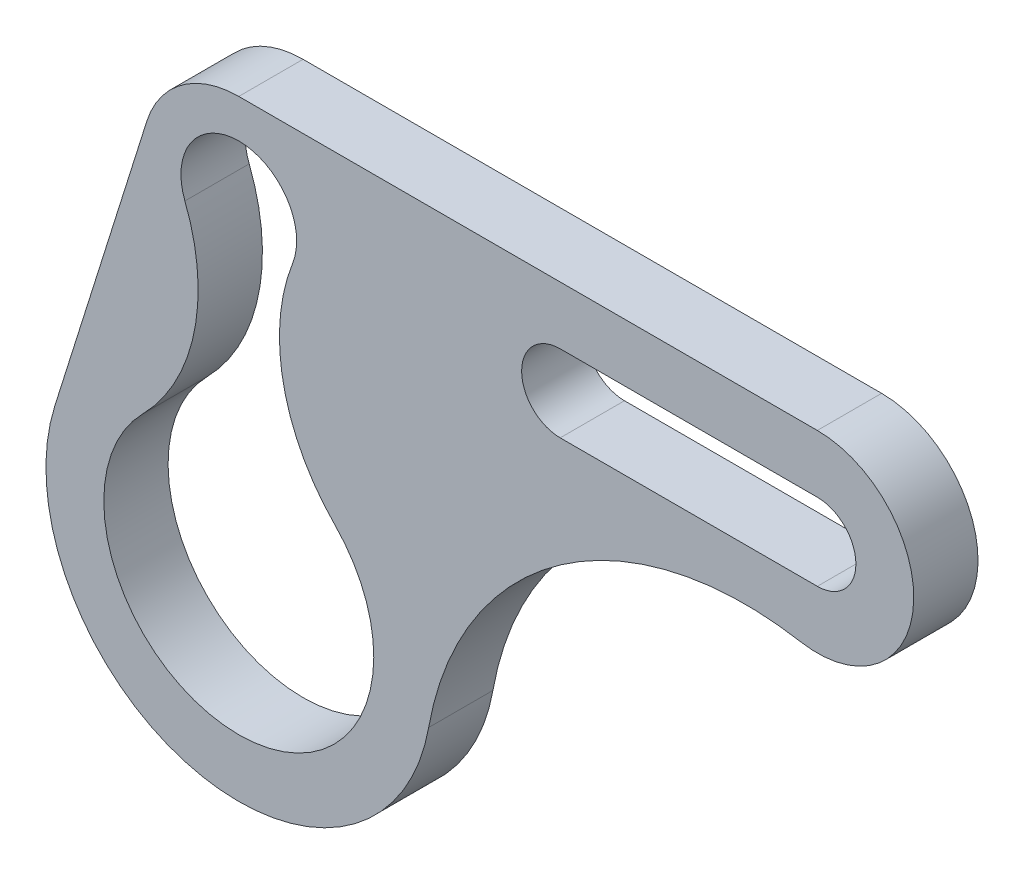
SolidWorks part; units mm, degrees
ref_plane "Front Plane" through (0, 0, 0) normal (0, 0, 1) x (1, 0, 0)
ref_plane "Top Plane" through (0, 0, 0) normal (0, 1, 0) x (1, 0, 0)
ref_plane "Right Plane" through (0, 0, 0) normal (1, 0, 0) x (0, 0, -1)
sketch "Sketch1" plane through (0, 0, 0) normal (0, 0, 1) x (1, 0, 0)
  line L0 (0, 65) -> (90, 65)
  line L1 (-14.3091, 54.5) -> (-28.6182, 9)
  line L2 (50, 50) -> (90, 50) construction
  line L3 (50, 56) -> (90, 56)
  line L4 (50, 44) -> (90, 44)
  line L5 (0, 50) -> (0, -21) construction
  arc A0 (0, 65) -> (-14.3091, 54.5) centre (0, 50) ccw
  arc A1 (-28.6182, 9) -> (29.5356, -5.2579) centre (0, 0) ccw
  arc A2 (8.3822, 46.7231) -> (-8.3822, 46.7231) centre (0, 50) ccw
  arc A3 (50, 56) -> (50, 44) centre (50, 50) ccw
  arc A4 (90, 44) -> (90, 56) centre (90, 50) ccw
  arc A5 (-14.9565, 14.7412) -> (14.9565, 14.7412) centre (0, 0) ccw
  arc A6 (-8.3822, 46.7231) -> (-14.9565, 14.7412) centre (-36.323, 35.8) cw
  arc A7 (8.3822, 46.7231) -> (14.9565, 14.7412) centre (36.323, 35.8) ccw
  arc A8 (90, 65) -> (87.4066, 35.2259) centre (90, 50) cw
  arc A9 (87.4066, 35.2259) -> (29.5356, -5.2579) centre (78.7617, -14.0211) ccw
  point P9 (0, 0)
  point P11 (70, 50)
  point P24 (0, 0)
  point P28 (0, -21)
  dimension "D1" = 15
  dimension "D2" = 18
  dimension "D3" = 6
  dimension "D6" = 42
  dimension "D8" = 50
  dimension "D9" = 30
  dimension "D10" = 15
  dimension "D11" = 30
  dimension "D12" = 50
  dimension "D4" = 40
  dimension "D5" = 50
  dimension "D7" = 90
extrude "Boss-Extrude1" add sketch "Sketch1" along normal mid plane 10
